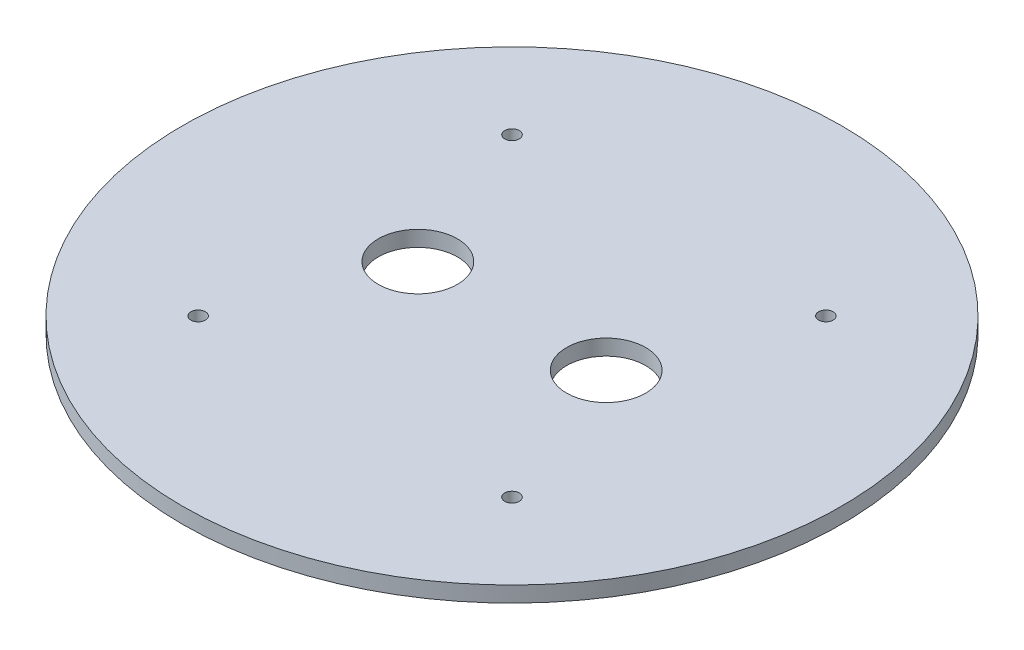
SolidWorks part; units mm, degrees
ref_plane "Front Plane" through (0, 0, 0) normal (0, 0, 1) x (1, 0, 0)
ref_plane "Top Plane" through (0, 0, 0) normal (0, 1, 0) x (1, 0, 0)
ref_plane "Right Plane" through (0, 0, 0) normal (1, 0, 0) x (0, 0, -1)
sketch "Sketch1" plane through (0, 0, 0) normal (0, 1, 0) x (1, 0, 0)
  line L0 (-55, 0) -> (55, 0) construction
  line L1 (0, -55) -> (0, 55) construction
  circle A0 centre (0, 0) radius 66.675
  dimension "D1" = 133.35
extrude "Boss-Extrude1" add sketch "Sketch1" along normal blind 3.175
hole_wizard "Hole1" positions "Sketch2" profile "Sketch3" legacy end condition through all
sketch "Sketch2" plane through (0, 3.175, 0) normal (0, 1, 0) x (1, 0, 0)
  line L0 (-1.7463, 0) -> (1.7463, 0) construction
  line L1 (0, -1.7463) -> (0, 1.7463) construction
  point P0 (19.05, 0)
  dimension "D1" = 19.05
sketch "Sketch3" plane through (19.05, 3.175, 0) normal (1, 0, 0) x (0, 0, 1)
  line L0 (0, 0) -> (0, 3.175)
  line L1 (0, 3.175) -> (8.001, 3.175)
  line L2 (8.001, 3.175) -> (8.001, 0)
  line L3 (8.001, 0) -> (0, 0)
  line L4 (0, 110) -> (0, -10) construction
  dimension "Diameter" = 16.002
  dimension "Depth" = 3.175
mirror "Mirror1" about plane through (0, 0, 0) normal (1, 0, 0) of "Hole1"
sketch "Sketch4" plane through (0, 3.175, 0) normal (0, 1, 0) x (1, 0, 0)
  line L1 (31.75, 31.75) -> (-31.75, 31.75)
  line L2 (31.75, 31.75) -> (31.75, -31.75)
  line L3 (31.75, -31.75) -> (-31.75, -31.75)
  line L4 (-31.75, 31.75) -> (-31.75, -31.75)
  line L5 (31.75, 31.75) -> (-31.75, -31.75) construction
  line L6 (31.75, -31.75) -> (-31.75, 31.75) construction
  point P0 (0, 0)
  dimension "D1" = 63.5
  dimension "D2" = 63.5
hole_wizard "#4 Clearance Hole1" positions "Sketch5" profile "Sketch6" hole size "#4" standard "ANSI Inch" end condition through all
sketch "Sketch5" plane through (0, 3.175, 0) normal (0, 1, 0) x (1, 0, 0)
  point P0 (-31.75, 31.75)
sketch "Sketch6" plane through (-31.75, 3.175, -31.75) normal (1, 0, 0) x (0, 0, 1)
  line L0 (0, 0) -> (0, 3.175)
  line L1 (0, 3.175) -> (1.4732, 3.175)
  line L2 (1.4732, 3.175) -> (1.4732, 0)
  line L5 (1.4732, 0) -> (0, 0)
  line L11 (0, -6.35) -> (0, 107.95) construction
  dimension "Thru Hole Dia." = 2.9464
  dimension "Thru Hole Depth" = 3.175
pattern_linear "LPattern1" count 2 spacing 63.5 along (1, 0, 0) count 2 spacing 63.5 along (0, 0, 1) of "#4 Clearance Hole1"
equation "\"D2@Sketch4\"=\"D1@Sketch4\""
